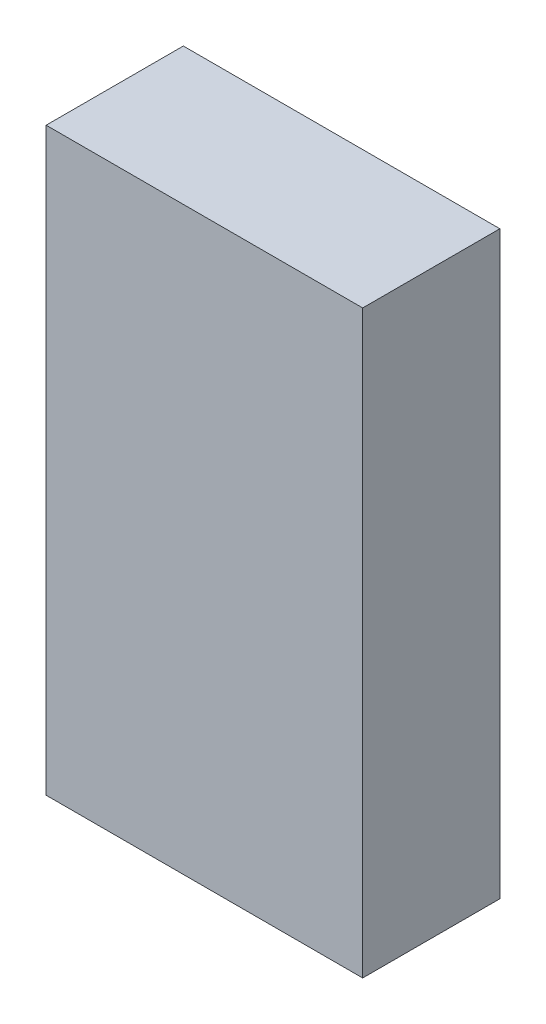
SolidWorks part; units mm, degrees
ref_plane "Front Plane" through (0, 0, 0) normal (0, 0, 1) x (1, 0, 0)
ref_plane "Top Plane" through (0, 0, 0) normal (0, 1, 0) x (1, 0, 0)
ref_plane "Right Plane" through (0, 0, 0) normal (1, 0, 0) x (0, 0, -1)
sketch "Sketch1" plane through (0, 0, 0) normal (0, 0, 1) x (1, 0, 0)
  line L1 (0, 0) -> (60, 0)
  line L2 (0, 0) -> (0, 110)
  line L3 (0, 110) -> (60, 110)
  line L4 (60, 0) -> (60, 110)
  dimension "D1" = 60
  dimension "D2" = 110
extrude "Boss-Extrude1" add sketch "Sketch1" along normal blind 26
